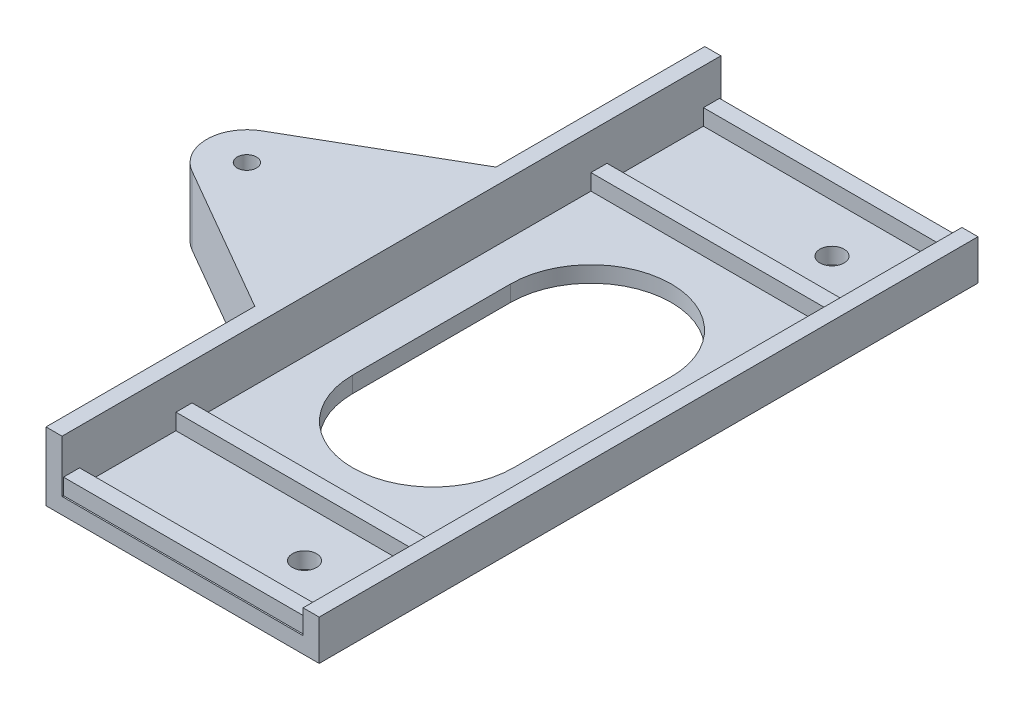
SolidWorks part; units mm, degrees
material "ABS"
ref_plane "Plan de face" through (0, 0, 0) normal (0, 0, 1) x (1, 0, 0)
ref_plane "Plan de dessus" through (0, 0, 0) normal (0, 1, 0) x (1, 0, 0)
ref_plane "Plan de droite" through (0, 0, 0) normal (1, 0, 0) x (0, 0, -1)
sketch "Esquisse1" plane through (0, 0, 0) normal (0, 0, 1) x (1, 0, 0)
  line L0 (0, 3) -> (0, 0)
  line L1 (0, 0) -> (-30, 0)
  line L2 (-30, 0) -> (-30, 6.5)
  dimension "D1" = 6.5
  dimension "D2" = 3
  dimension "D3" = 30
extrude "Extru.-Mince1" add sketch "Esquisse1" along normal mid plane 82 thin thin type one direction reverse wall 2
sketch "Esquisse2" plane through (0, 0, 0) normal (0, 1, 0) x (1, 0, 0)
  line L0 (-32, 0) -> (2, 0) construction
  line L1 (-32, -41) -> (-32, 41) construction
  line L2 (2, -41) -> (2, 41) construction
  line L3 (0, -41) -> (0, 41) construction
  circle A0 centre (-8, -32.825) radius 1.5
  circle A1 centre (-8, 32.825) radius 1.5
  dimension "D1" = 8
  dimension "D2" = 65.65
  dimension "D3" = 3
extrude "Enlèv. mat.-Extru.1" cut sketch "Esquisse2" against normal through all
sketch "Esquisse3" plane through (0, 0, 0) normal (0, 1, 0) x (1, 0, 0)
  line L0 (-30, -41) -> (-30, 41) construction
  line L1 (-30, 26.825) -> (0, 26.825)
  line L2 (-30, 26.825) -> (-30, 24.825)
  line L3 (-30, 24.825) -> (0, 24.825)
  line L4 (0, 26.825) -> (0, 24.825)
  line L5 (0, -41) -> (0, 41) construction
  line L6 (-32, 0) -> (2, 0) construction
  line L7 (-32, -41) -> (-32, 41) construction
  line L8 (2, -41) -> (2, 41) construction
  line L9 (0, -26.825) -> (0, -24.825)
  line L10 (-30, -24.825) -> (0, -24.825)
  line L11 (-30, -26.825) -> (-30, -24.825)
  line L12 (-30, -26.825) -> (0, -26.825)
  line L13 (0, 41) -> (2, 41) construction
  line L14 (0, -40.825) -> (0, -38.825)
  line L15 (-30, 40.825) -> (0, 40.825)
  line L16 (-30, 40.825) -> (-30, 38.825)
  line L17 (-30, 38.825) -> (0, 38.825)
  line L18 (0, 40.825) -> (0, 38.825)
  line L19 (-30, -38.825) -> (0, -38.825)
  line L20 (-30, -40.825) -> (-30, -38.825)
  line L21 (-30, -40.825) -> (0, -40.825)
  circle A0 centre (-8, 32.825) radius 1.5 construction
  dimension "D1" = 6
  dimension "D2" = 6
extrude "Boss.-Extru.1" add sketch "Esquisse3" along normal blind 2
sketch "Esquisse4" plane through (0, 0, 0) normal (0, 1, 0) x (1, 0, 0)
  line L0 (-15, 9.825) -> (-15, -9.825) construction
  line L1 (-5, 9.825) -> (-5, -9.825)
  line L2 (-25, 9.825) -> (-25, -9.825)
  line L3 (0, -24.825) -> (0, 24.825) construction
  line L4 (-30, -24.825) -> (-30, 24.825) construction
  line L5 (-30, 24.825) -> (0, 24.825) construction
  arc A0 (-5, 9.825) -> (-25, 9.825) centre (-15, 9.825) ccw
  arc A1 (-25, -9.825) -> (-5, -9.825) centre (-15, -9.825) ccw
  point P2 (-15, 0)
  dimension "D3" = 5
  dimension "D1" = 5
  dimension "D2" = 5
extrude "Enlèv. mat.-Extru.2" cut sketch "Esquisse4" against normal through all
sketch "Esquisse5" plane through (0, 6.5, 0) normal (0, 1, 0) x (1, 0, 0)
  line L0 (-50.5, 4.3301) -> (-32, 15.0111)
  line L1 (-32, -41) -> (-32, 41) construction
  line L2 (-32, 15.0111) -> (-32, -15.0111)
  line L3 (-32, -15.0111) -> (-50.5, -4.3301)
  circle A0 centre (-48, 0) radius 1.2
  arc A1 (-50.5, 4.3301) -> (-50.5, -4.3301) centre (-48, 0) ccw
  circle A2 centre (-8, -32.825) radius 1.5 construction
  point P7 (-32, 0)
  dimension "D1" = 10
  dimension "D2" = 2.4
  dimension "D3" = 40
  dimension "D4" = 60
extrude "Boss.-Extru.2" add sketch "Esquisse5" against normal up to surface (8.5 mm away) up to face at (-15, -2, 0)
